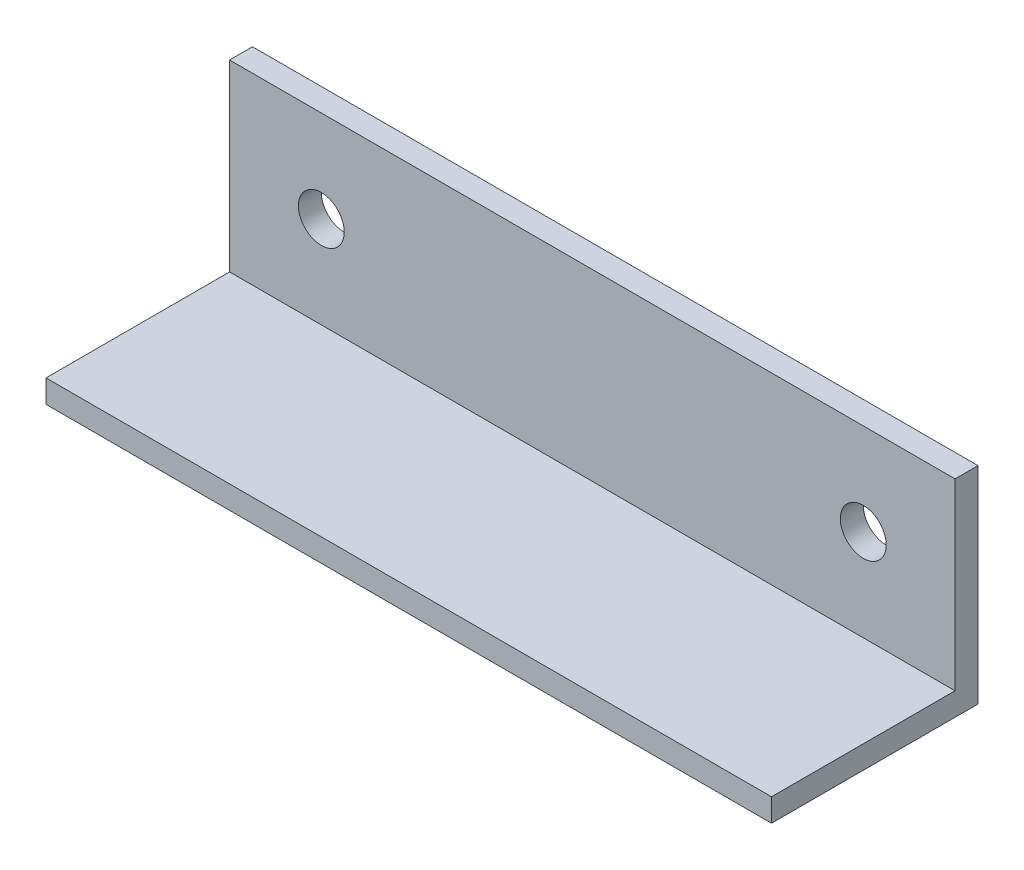
SolidWorks part; units mm, degrees
ref_plane "Front Plane" through (0, 0, 0) normal (0, 0, 1) x (1, 0, 0)
ref_plane "Top Plane" through (0, 0, 0) normal (0, 1, 0) x (1, 0, 0)
ref_plane "Right Plane" through (0, 0, 0) normal (1, 0, 0) x (0, 0, -1)
sketch "Sketch1" plane through (0, 0, 0) normal (0, 0, 1) x (1, 0, 0)
  line L1 (-12.7, 12.7) -> (87.7, 12.7)
  line L2 (-12.7, 12.7) -> (-12.7, -15.875)
  line L3 (-12.7, -15.875) -> (87.7, -15.875)
  line L4 (87.7, 12.7) -> (87.7, -15.875)
  circle A0 centre (0, 0) radius 3.175
  circle A1 centre (75, 0) radius 3.175
  point P8 (80.9314, 25.7509)
  point P9 (-31.4362, 11.1812)
  point P10 (0, 0)
  point P12 (-13.2433, 14.5141)
  dimension "D1" = 6.35
  dimension "D2" = 6.35
  dimension "D3" = 75
  dimension "D4" = 0
  dimension "D5" = 12.7
  dimension "D6" = 12.7
  dimension "D7" = 15.875
  dimension "D8" = 12.7
extrude "Boss-Extrude1" add sketch "Sketch1" along normal blind 3.175
sketch "Sketch2" plane through (0, 0, 3.175) normal (0, 0, 1) x (1, 0, 0)
  line L0 (87.7, -15.875) -> (87.7, 12.7) construction
  line L1 (-12.7, -15.875) -> (87.7, -15.875)
  line L2 (-12.7, -15.875) -> (-12.7, -12.7)
  line L3 (-12.7, -12.7) -> (87.7, -12.7)
  line L4 (87.7, -15.875) -> (87.7, -12.7)
  dimension "D1" = 3.175
extrude "Boss-Extrude2" add sketch "Sketch2" along normal blind 25.4
